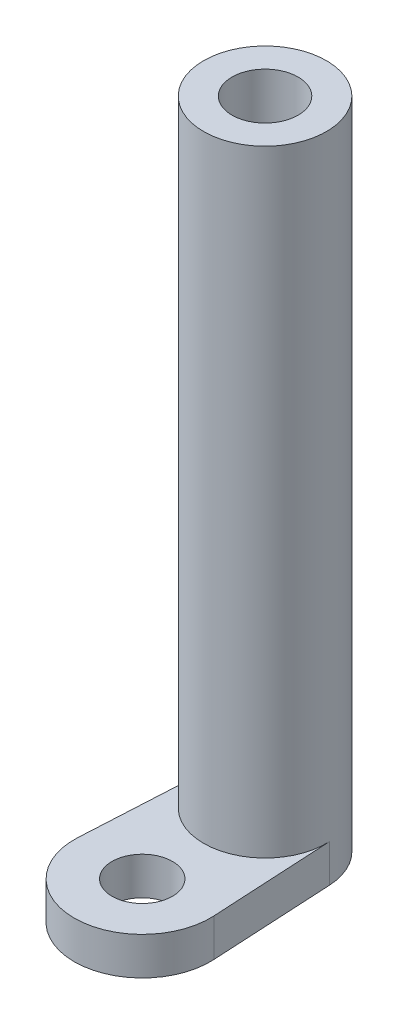
SolidWorks part; units mm, degrees
ref_plane "Front Plane" through (0, 0, 0) normal (0, 0, 1) x (1, 0, 0)
ref_plane "Top Plane" through (0, 0, 0) normal (0, 1, 0) x (1, 0, 0)
ref_plane "Right Plane" through (0, 0, 0) normal (1, 0, 0) x (0, 0, -1)
sketch "Sketch1" plane through (0, 0, 0) normal (0, 1, 0) x (1, 0, 0)
  circle A0 centre (0, 0) radius 1.75
  circle A1 centre (0, 0) radius 3.25
  dimension "D1" = 3.5
  dimension "D2" = 1.5
extrude "Boss-Extrude1" add sketch "Sketch1" along normal up to surface (34.625 mm away)
sketch "Sketch2" plane through (0, 0, 0) normal (0, 1, 0) x (1, 0, 0)
  line L0 (-3.5948, -6.3062) -> (-3.2453, 0.175)
  line L1 (3.5948, -6.3062) -> (3.2453, 0.175)
  circle A0 centre (0, 0) radius 3.25 construction
  circle A1 centre (0, 0) radius 1.75 construction
  arc A2 (3.2453, 0.175) -> (-3.2453, 0.175) centre (0, 0) ccw
  circle A3 centre (0, 0) radius 1.75
  circle A4 centre (0, -6.5) radius 1.6
  arc A5 (-3.5948, -6.3062) -> (3.5948, -6.3062) centre (0, -6.5) ccw
  dimension "D1" = 3.2
  dimension "D3" = 2
  dimension "D2" = 6.5
extrude "Boss-Extrude2" add sketch "Sketch2" along normal blind 2
